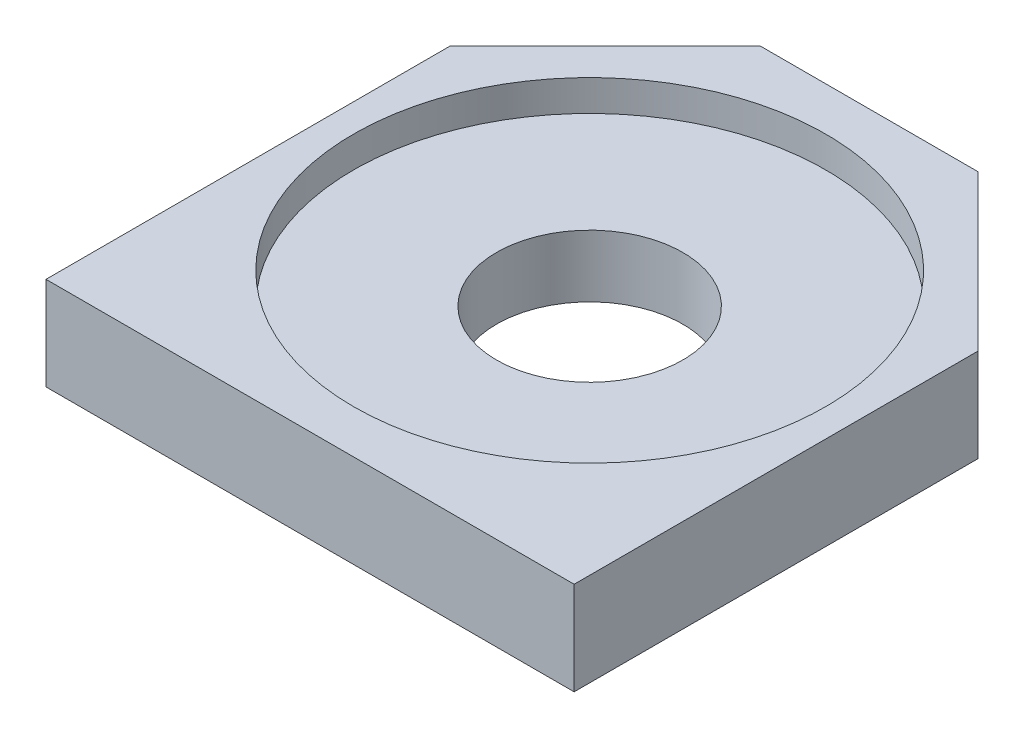
SolidWorks part; units mm, degrees
ref_plane "前视基准面" through (0, 0, 0) normal (0, 0, 1) x (1, 0, 0)
ref_plane "上视基准面" through (0, 0, 0) normal (0, 1, 0) x (1, 0, 0)
ref_plane "右视基准面" through (0, 0, 0) normal (1, 0, 0) x (0, 0, -1)
other "Configuration Table"
sketch "草图1" plane through (0, 0, 0) normal (0, 1, 0) x (1, 0, 0)
  line L1 (-85, -90) -> (85, -90)
  line L2 (-85, -90) -> (-85, 90)
  line L3 (-85, 90) -> (85, 90)
  line L4 (85, -90) -> (85, 90)
  line L5 (-85, -90) -> (85, 90) construction
  line L6 (-85, 90) -> (85, -90) construction
  point P0 (0, 0)
  dimension "D1" = 180
  dimension "D2" = 170
extrude "凸台-拉伸1" add sketch "草图1" along normal blind 30
chamfer "倒角1" distance 50 angle 45 2 edges at (85, 15, -90) (-85, 15, -90)
sketch "草图3" plane through (0, 30, 0) normal (0, 1, 0) x (1, 0, 0)
  circle A0 centre (0, 0) radius 76
extrude "切除-拉伸1" cut sketch "草图3" against normal blind 10
sketch "草图4" plane through (0, 20, 0) normal (0, 1, 0) x (1, 0, 0)
  circle A0 centre (0, 0) radius 30
extrude "切除-拉伸2" cut sketch "草图4" against normal through all
sketch "草图5" plane through (0, 0, -90) normal (0, 0, -1) x (-1, 0, 0)
  line L1 (-20, 20) -> (20, 20)
  line L2 (-20, 20) -> (-20, 5)
  line L3 (-20, 5) -> (20, 5)
  line L4 (20, 20) -> (20, 5)
  line L5 (-20, 20) -> (20, 5) construction
  line L6 (-20, 5) -> (20, 20) construction
  line L7 (-35, 0) -> (35, 0) construction
  point P0 (0, 12.5)
  point P5 (1.4318, 13.493)
  point P6 (0, 14.3879)
  point P7 (0, 0)
  dimension "D1" = 40
  dimension "D2" = 15
  dimension "D3" = 5
extrude "切除-拉伸3" cut sketch "草图5" against normal blind 10
